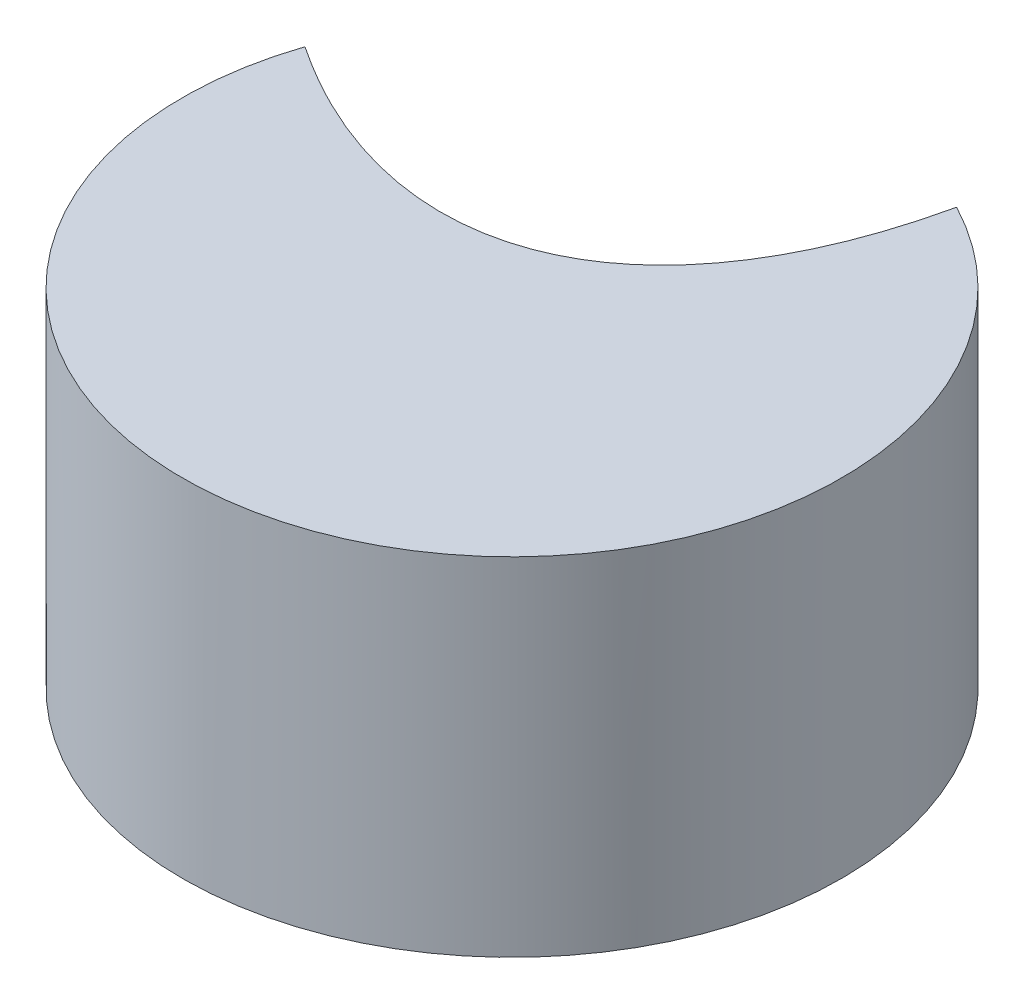
SolidWorks part; units mm, degrees
other "Moving Steel Cup Liner 3"
ref_plane "Front Plane" through (0, 0, 0) normal (0, 0, 1) x (1, 0, 0)
ref_plane "Top Plane" through (0, 0, 0) normal (0, 1, 0) x (1, 0, 0)
ref_plane "Right Plane" through (0, 0, 0) normal (1, 0, 0) x (0, 0, -1)
sketch3d "Keyed Back Sketch datum points"
  point P0 (-56.2917, -97, 0)
  point P1 (-46.2917, -97, 0)
  point P2 (-56.2917, -97, 10)
ref_plane "Keyed Back Sketch plane" through (0, -97, 0) normal (0, -1, 0) x (-1, 0, 0)
sketch "Keyed Back Sketch" plane through (0, -97, 0) normal (0, -1, 0) x (-1, 0, 0)
  line L0 (59.8116, -28.5681) -> (55.7718, -26.2357)
  arc A0 (55.7718, -26.2357) -> (59.8116, -28.5681) centre (56.2917, -30) ccw
extrude "Keyed Back" add sketch "Keyed Back Sketch" along normal blind 0.7 separate body
sketch3d "Cup Blank Sketch datum points"
  point P0 (-56.2917, -97.7, 0)
  point P1 (-46.2917, -97.7, 0)
  point P2 (-56.2917, -97.7, 10)
ref_plane "Cup Blank Sketch plane" through (0, -97.7, 0) normal (0, -1, 0) x (-1, 0, 0)
sketch "Cup Blank Sketch" plane through (0, -97.7, 0) normal (0, -1, 0) x (-1, 0, 0)
  circle A0 centre (56.2917, -30) radius 3.8
extrude "Cup Blank" add sketch "Cup Blank Sketch" along normal blind 3.3
sketch3d "Spherical Bearing Seat axis line"
  line L0 (-56.2917, -101, 20) -> (-56.2917, -101, 40) construction
ref_axis "Spherical Bearing Seat axis" through (-56.2917, -101, 20) along (0, 0, 1)
sketch3d "Spherical Bearing Seat profile datum points"
  point P0 (-56.2917, -101, 30)
  point P1 (-46.2917, -101, 30)
  point P2 (-56.2917, -101, 40)
ref_plane "Spherical Bearing Seat profile plane" through (0, -101, 0) normal (0, -1, 0) x (-1, 0, 0)
sketch "Spherical Bearing Seat profile" plane through (0, -101, 0) normal (0, -1, 0) x (-1, 0, 0)
  line L0 (56.2917, -33.1) -> (56.2917, -26.9)
  arc A0 (56.2917, -26.9) -> (56.2917, -33.1) centre (56.2917, -30) ccw
revolve "Spherical Bearing Seat" cut sketch "Spherical Bearing Seat profile" angle 360 about axis through (-56.2917, -101, 20) along (0, 0, 1)
sketch3d "Articulation Throat axis line"
  line L0 (-53.1481, -106.3831, 37.8192) -> (-59.4352, -95.6169, 22.1808) construction
ref_axis "Articulation Throat axis" through (-53.1481, -106.3831, 37.8192) along (-0.3144, 0.5383, -0.7819)
sketch3d "Articulation Throat Sketch datum points"
  point P0 (-56.2917, -101, 30)
  point P1 (-56.2917, -109.2368, 24.3295)
  point P2 (-59.4352, -95.6169, 22.1808)
ref_plane "Articulation Throat Sketch plane" through (-75.1941, -14.1195, 20.5094) normal (0.9493, 0.1783, -0.2589) x (-0.2545, -0.0478, -0.9659)
sketch "Articulation Throat Sketch" plane through (-75.1941, -14.1195, 20.5094) normal (0.9493, 0.1783, -0.2589) x (-0.2545, -0.0478, -0.9659)
  line L0 (-9.8257, -88.8766) -> (-8.4754, -90.7385)
  line L1 (-8.4754, -90.7385) -> (14.089, -82.6758)
  line L2 (14.089, -82.6758) -> (8.7936, -75.3739)
  line L3 (8.7936, -75.3739) -> (-9.8257, -88.8766)
revolve "Articulation Throat" cut sketch "Articulation Throat Sketch" angle 360 about axis through (-53.1481, -106.3831, 37.8192) along (-0.3144, 0.5383, -0.7819)
